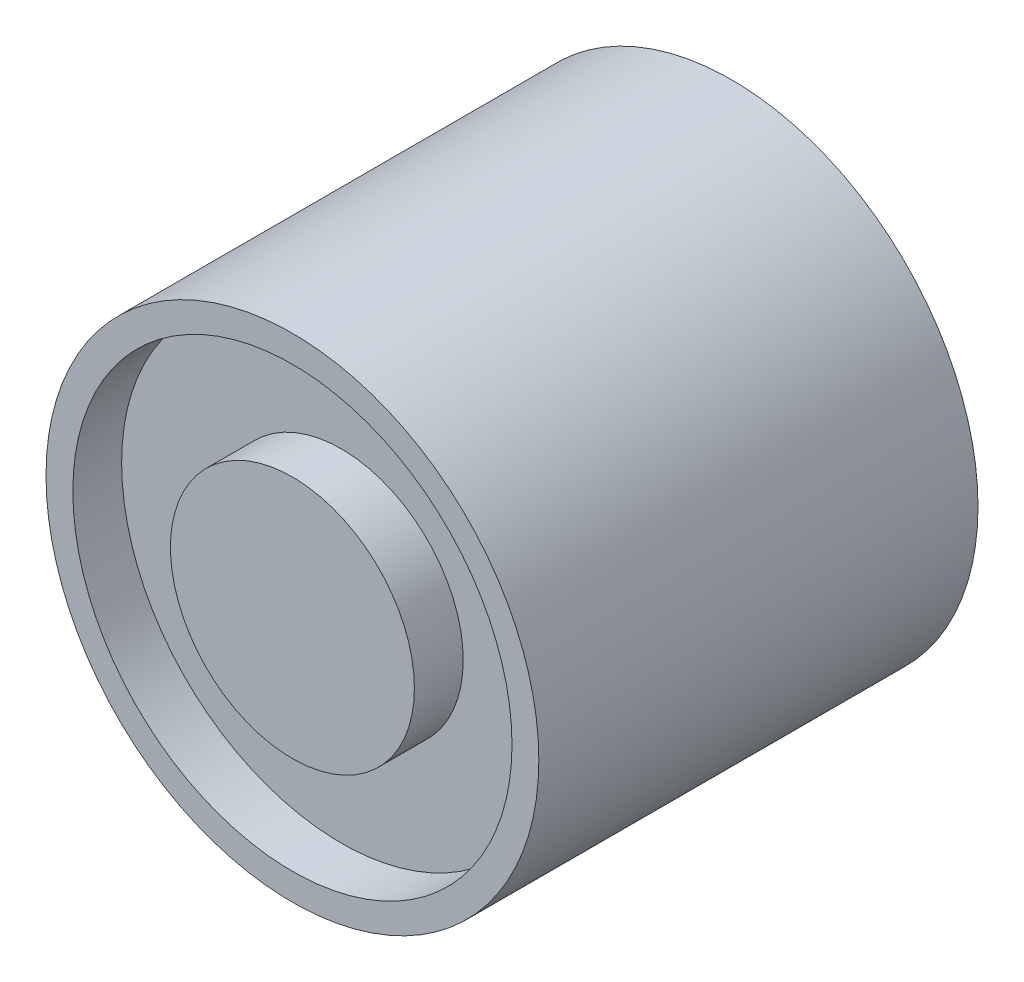
SolidWorks part; units mm, degrees
ref_plane "Front Plane" through (0, 0, 0) normal (0, 0, 1) x (1, 0, 0)
ref_plane "Top Plane" through (0, 0, 0) normal (0, 1, 0) x (1, 0, 0)
ref_plane "Right Plane" through (0, 0, 0) normal (1, 0, 0) x (0, 0, -1)
sketch "Sketch1" plane through (0, 0, 0) normal (0, 0, 1) x (1, 0, 0)
  circle A0 centre (0, 0) radius 12.827
extrude "Boss-Extrude1" add sketch "Sketch1" along normal blind 20.32
sketch "Sketch2" plane through (0, 0, 20.32) normal (0, 0, 1) x (1, 0, 0)
  circle A0 centre (0, 0) radius 6.35
  circle A1 centre (0, 0) radius 11.43
  circle A2 centre (0, 0) radius 12.827
  circle M2 centre (0, 0) radius 12.827
extrude "Boss-Extrude2" add sketch "Sketch2" along normal blind 2.54 contours A1 M2 | A0
